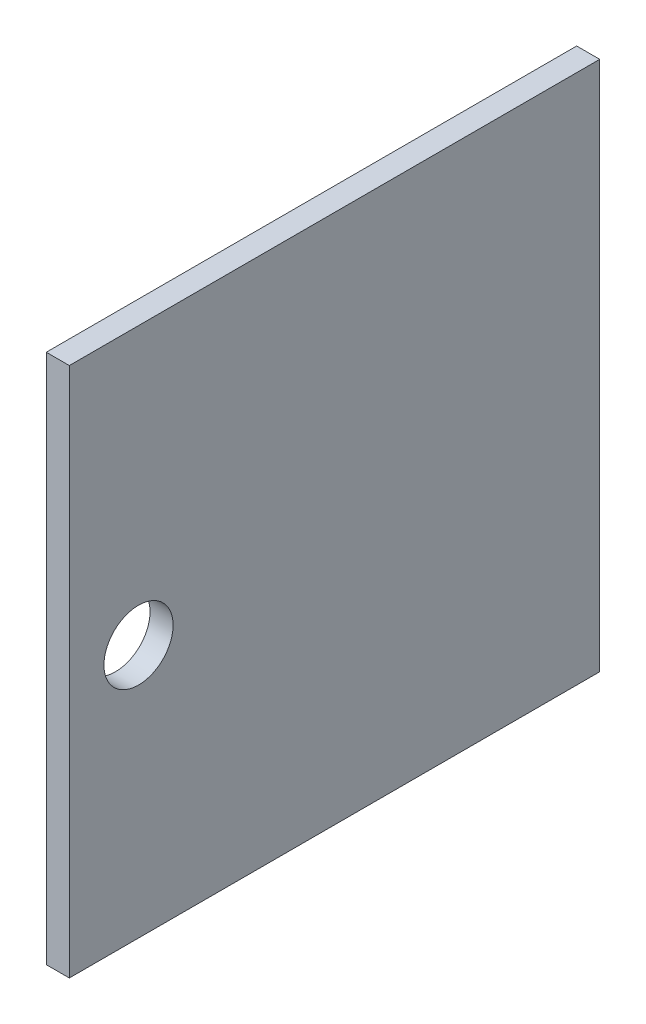
SolidWorks part; units mm, degrees
ref_plane "前基準面" through (0, 0, 0) normal (0, 0, 1) x (1, 0, 0)
ref_plane "上基準面" through (0, 0, 0) normal (0, 1, 0) x (1, 0, 0)
ref_plane "右基準面" through (0, 0, 0) normal (1, 0, 0) x (0, 0, -1)
sketch "草圖1" plane through (0, 0, 0) normal (1, 0, 0) x (0, 0, -1)
  line L1 (-38.4868, 109.1118) -> (76.5132, 109.1118)
  line L2 (-38.4868, 109.1118) -> (-38.4868, -5.8882)
  line L3 (-38.4868, -5.8882) -> (76.5132, -5.8882)
  line L4 (76.5132, 109.1118) -> (76.5132, -5.8882)
  circle A0 centre (-23.4868, 49.1118) radius 7.5
  point P6 (-9.1517, 58.2232)
  dimension "D3" = 15
  dimension "D1" = 115
  dimension "D2" = 115
  dimension "D4" = 55
  dimension "D5" = 15
extrude "填料-伸長1" add sketch "草圖1" against normal blind 5
